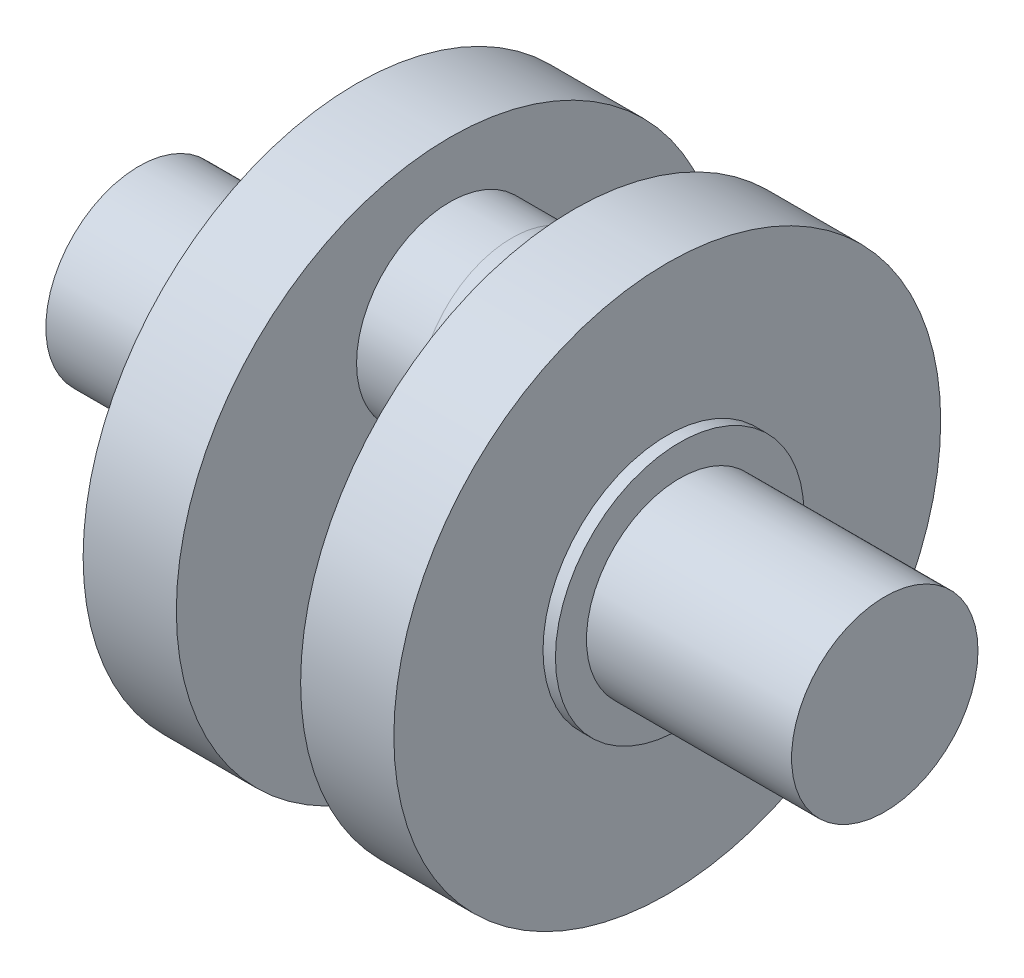
SolidWorks part; units mm, degrees
ref_plane "Płaszczyzna przednia" through (0, 0, 0) normal (0, 0, 1) x (1, 0, 0)
ref_plane "Płaszczyzna górna" through (0, 0, 0) normal (0, 1, 0) x (1, 0, 0)
ref_plane "Płaszczyzna prawa" through (0, 0, 0) normal (1, 0, 0) x (0, 0, -1)
sketch "Szkic1" plane through (0, 0, 0) normal (1, 0, 0) x (0, 0, -1)
  circle A0 centre (0, 0) radius 15
  dimension "D1" = 30
extrude "Dodanie-wyciągnięcie1" add sketch "Szkic1" along normal blind 33
sketch "Szkic4" plane through (0, 0, 0) normal (1, 0, 0) x (0, 0, -1)
  circle A0 centre (0, 0) radius 20
  dimension "D1" = 40
extrude "Dodanie-wyciągnięcie2" add sketch "Szkic4" against normal blind 2
ref_plane "Płaszczyzna1" through (-2, 0, 0) normal (-1, 0, 0) x (0, 0, 1)
sketch "Szkic6" plane through (-2, 0, 0) normal (-1, 0, 0) x (0, 0, 1)
  circle A0 centre (0, 0) radius 44
  dimension "D1" = 88
extrude "Dodanie-wyciągnięcie4" add sketch "Szkic6" along normal blind 15
ref_plane "Płaszczyzna2" through (-17, 0, 0) normal (-1, 0, 0) x (0, 0, 1)
sketch "Szkic7" plane through (-17, 0, 0) normal (-1, 0, 0) x (0, 0, 1)
  circle A0 centre (0, 20) radius 15
  dimension "D2" = 30
  dimension "D1" = 20
extrude "Dodanie-wyciągnięcie5" add sketch "Szkic7" along normal blind 10
mirror "Lustro1" about plane through (-27, 20, 0) normal (-1, 0, 0) of bodies 105
